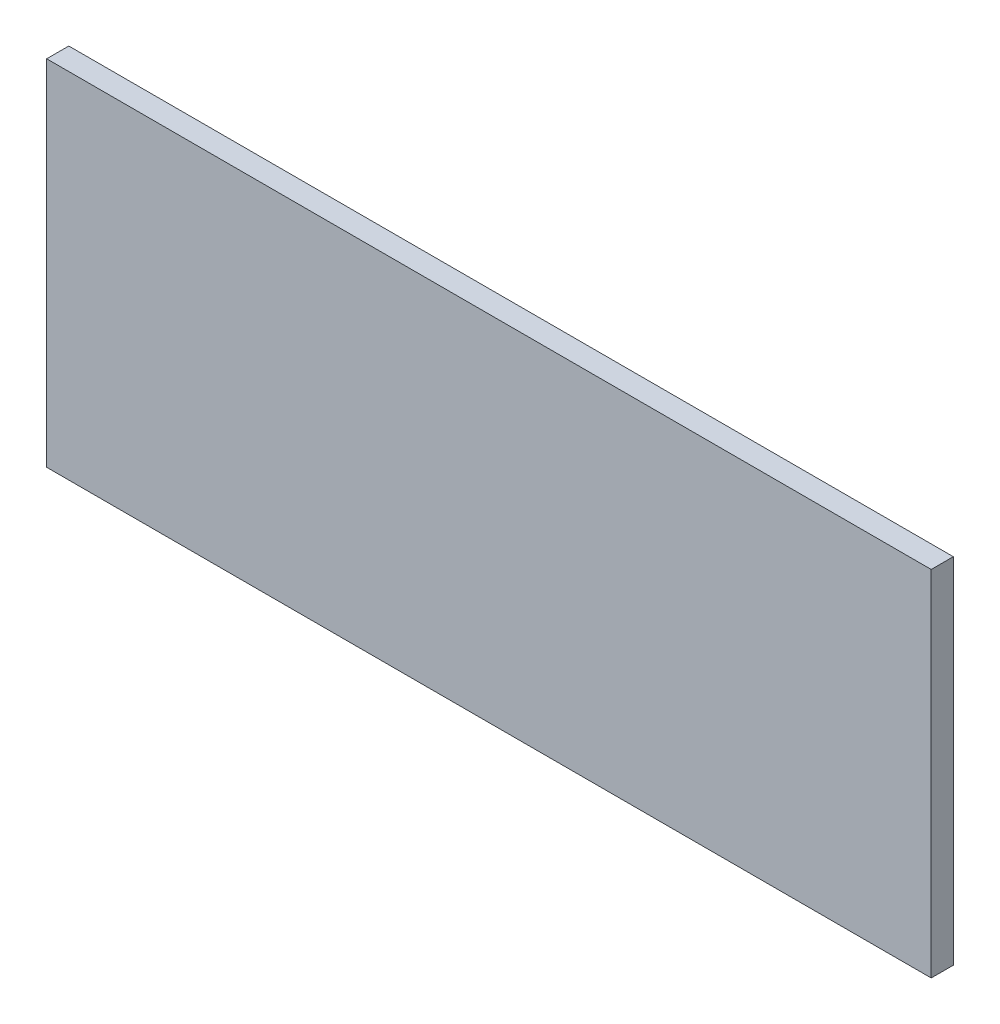
SolidWorks part; units mm, degrees
ref_plane "前视基准面" through (0, 0, 0) normal (0, 0, 1) x (1, 0, 0)
ref_plane "上视基准面" through (0, 0, 0) normal (0, 1, 0) x (1, 0, 0)
ref_plane "右视基准面" through (0, 0, 0) normal (1, 0, 0) x (0, 0, -1)
sketch "草图1" plane through (0, 0, 0) normal (0, 0, 1) x (1, 0, 0)
  line L1 (-100, 40) -> (100, 40)
  line L2 (-100, 40) -> (-100, -40)
  line L3 (-100, -40) -> (100, -40)
  line L4 (100, 40) -> (100, -40)
  line L5 (-100, 40) -> (100, -40) construction
  line L6 (-100, -40) -> (100, 40) construction
  point P0 (0, 0)
  dimension "D1" = 200
  dimension "D2" = 80
extrude "凸台-拉伸1" add sketch "草图1" along normal mid plane 5
